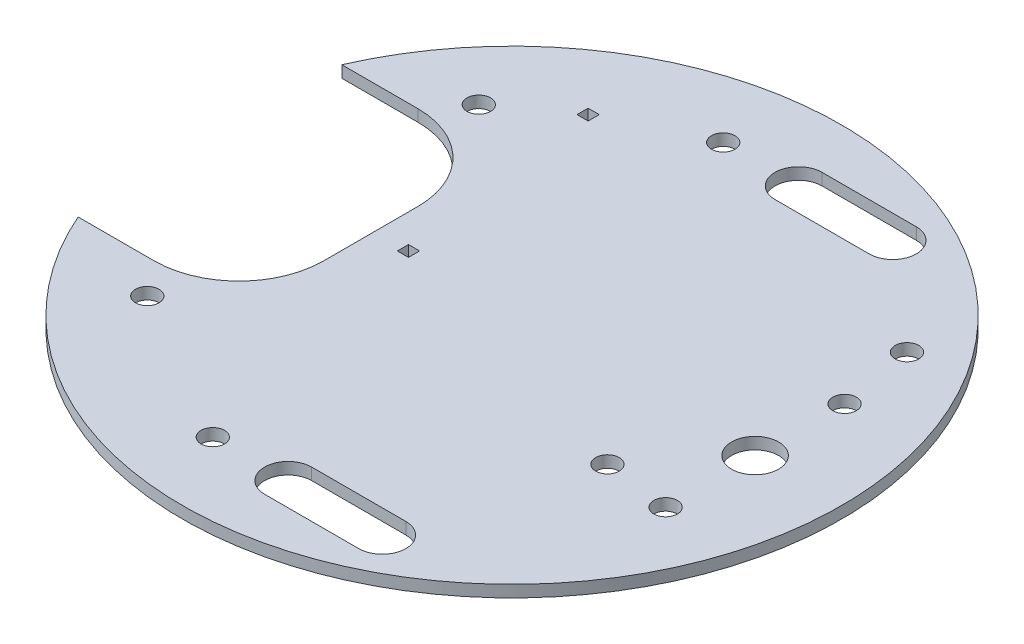
SolidWorks part; units mm, degrees
ref_plane "Front Plane" through (0, 0, 0) normal (0, 0, 1) x (1, 0, 0)
ref_plane "Top Plane" through (0, 0, 0) normal (0, 1, 0) x (1, 0, 0)
ref_plane "Right Plane" through (0, 0, 0) normal (1, 0, 0) x (0, 0, -1)
sketch "Sketch1" plane through (0, 0, 0) normal (0, 1, 0) x (1, 0, 0)
  line L0 (0, 0) -> (109.2336, 0) construction
  line L1 (0, 0) -> (-110.6657, 0) construction
  line L2 (27.076, -24.13) -> (65.5497, -24.13)
  line L3 (27.076, -24.13) -> (27.076, 24.13)
  line L4 (27.076, 24.13) -> (65.5497, 24.13)
  line L5 (65.5497, -24.13) -> (65.5497, 24.13)
  line L6 (27.076, -24.13) -> (65.5497, 24.13) construction
  line L7 (27.076, 24.13) -> (65.5497, -24.13) construction
  line L9 (-88.9, 35.56) -> (-38.1, 35.56)
  line L10 (-88.9, 35.56) -> (-88.9, -35.56)
  line L11 (-88.9, -35.56) -> (-38.1, -35.56)
  line L12 (-38.1, 35.56) -> (-38.1, -35.56)
  line L13 (-88.9, 35.56) -> (-38.1, -35.56) construction
  line L14 (-88.9, -35.56) -> (-38.1, 35.56) construction
  circle A0 centre (0, 0) radius 88.9
  circle A1 centre (0, 0) radius 69.85
  circle A2 centre (65.5497, 24.13) radius 3.175
  circle A3 centre (65.5497, -24.13) radius 3.175
  circle A4 centre (-53.6721, -44.7027) radius 3.175
  circle A5 centre (-11.8777, -68.8327) radius 3.175
  circle A6 centre (-11.8777, 68.8327) radius 3.175
  circle A7 centre (-53.6721, 44.7027) radius 3.175
  point P4 (46.3129, 0)
  point P12 (-63.5, 0)
  point P23 (0, 0)
  dimension "D1" = 177.8
  dimension "D2" = 139.7
  dimension "D4" = 3
  dimension "D3" = 48.26
  dimension "D5" = 71.12
  dimension "D6" = 50.8
  dimension "D7" = 63.5
sketch "Sketch2" plane through (0, 0, 0) normal (0, 1, 0) x (1, 0, 0)
  circle A0 centre (0, 0) radius 88.9
extrude "Boss-Extrude1" add sketch "Sketch2" along normal blind 3.175
sketch "Sketch3" plane through (0, 3.175, 0) normal (0, 1, 0) x (1, 0, 0)
  line L4 (27.076, -24.13) -> (65.5497, -24.13)
  line L5 (65.5497, -24.13) -> (65.5497, 24.13)
  line L6 (65.5497, 24.13) -> (27.076, 24.13)
  line L7 (27.076, 24.13) -> (27.076, -24.13)
  line L8 (27.076, -24.13) -> (65.5497, -24.13)
  line L9 (65.5497, -24.13) -> (65.5497, 24.13)
  line L10 (65.5497, 24.13) -> (27.076, 24.13)
  line L11 (27.076, 24.13) -> (27.076, -24.13)
  line L12 (-38.1, 35.56) -> (-88.9, 35.56)
  line L13 (-38.1, -35.56) -> (-38.1, 35.56)
  line L14 (-88.9, -35.56) -> (-38.1, -35.56)
  line L15 (-88.9, 35.56) -> (-88.9, -35.56)
  line L16 (-38.1, 35.56) -> (-88.9, 35.56)
  line L17 (-38.1, -35.56) -> (-38.1, 35.56)
  line L18 (-88.9, -35.56) -> (-38.1, -35.56)
  line L19 (-88.9, 35.56) -> (-88.9, -35.56)
  circle A1 centre (65.5497, -24.13) radius 3.175
  circle A2 centre (65.5497, -24.13) radius 3.175
  circle A3 centre (65.5497, 24.13) radius 3.175
  circle A4 centre (65.5497, 24.13) radius 3.175
  circle A5 centre (0, 0) radius 69.85
  circle A6 centre (0, 0) radius 69.85
  circle A7 centre (0, 0) radius 88.9
  circle A8 centre (0, 0) radius 88.9
  circle A9 centre (-53.6721, 44.7027) radius 3.175
  circle A10 centre (-53.6721, 44.7027) radius 3.175
  circle A11 centre (-11.8777, 68.8327) radius 3.175
  circle A12 centre (-11.8777, 68.8327) radius 3.175
  circle A13 centre (-11.8777, -68.8327) radius 3.175
  circle A14 centre (-11.8777, -68.8327) radius 3.175
  circle A15 centre (-53.6721, -44.7027) radius 3.175
  circle A16 centre (-53.6721, -44.7027) radius 3.175
  dimension "D1" = 0
  dimension "D2" = 0
  dimension "D3" = 0
  dimension "D4" = 0
  dimension "D5" = 0
  dimension "D6" = 0
  dimension "D7" = 0
  dimension "D8" = 0
  dimension "D9" = 0
  dimension "D10" = 0
extrude "Cut-Extrude1" cut sketch "Sketch3" against normal blind 3.175 contours A10 | A12 | A4 | A2 | A14 | A16 | L16 L19 L18 L17
sketch "Sketch4" plane through (0, 3.175, 0) normal (0, 1, 0) x (1, 0, 0)
  line L0 (0, 88.9) -> (0, -88.9) construction
  line L1 (88.9, 0) -> (-87.6104, 0) construction
  line L2 (52.695, -25.135) -> (52.695, -18.785)
  line L3 (-30.48, 2.54) -> (47.52, 2.54)
  line L4 (-30.48, 2.54) -> (-30.48, -57.46)
  line L5 (-30.48, -57.46) -> (47.52, -57.46)
  line L6 (47.52, 2.54) -> (47.52, -57.46)
  line L7 (-38.1, 58.62) -> (56.9, 58.62)
  line L8 (-38.1, 58.62) -> (-38.1, 7.62)
  line L9 (-38.1, 7.62) -> (56.9, 7.62)
  line L10 (56.9, 58.62) -> (56.9, 7.62)
  line L11 (56.9, 58.62) -> (53.9, 58.62)
  line L12 (56.9, 58.62) -> (56.9, 7.62)
  line L13 (56.9, 7.62) -> (53.9, 7.62)
  line L14 (53.9, 58.62) -> (53.9, 7.62)
  line L15 (56.9, 58.62) -> (61.9, 58.62)
  line L16 (56.9, 58.62) -> (56.9, 44.62)
  line L17 (56.9, 44.62) -> (61.9, 44.62)
  line L18 (61.9, 58.62) -> (61.9, 44.62)
  line L19 (47.52, 2.54) -> (44.52, 2.54)
  line L20 (47.52, 2.54) -> (47.52, -57.46)
  line L21 (47.52, -57.46) -> (44.52, -57.46)
  line L22 (44.52, 2.54) -> (44.52, -57.46)
  line L23 (47.52, 2.54) -> (47.695, 2.54)
  line L24 (47.52, 2.54) -> (47.52, -21.96)
  line L25 (47.52, -21.96) -> (47.695, -21.96)
  line L26 (47.695, 2.54) -> (47.695, -21.96)
  line L27 (52.695, -25.135) -> (42.695, -25.135)
  line L28 (52.695, -18.785) -> (42.695, -18.785)
  line L29 (42.695, -25.135) -> (42.695, -18.785)
  line L30 (52.695, -25.135) -> (42.695, -18.785) construction
  line L31 (52.695, -18.785) -> (42.695, -25.135) construction
  line L32 (69.9, 41.445) -> (69.9, 47.795)
  line L33 (69.9, 41.445) -> (53.9, 41.445)
  line L34 (69.9, 47.795) -> (53.9, 47.795)
  line L35 (53.9, 41.445) -> (53.9, 47.795)
  line L36 (69.9, 41.445) -> (53.9, 47.795) construction
  line L37 (69.9, 47.795) -> (53.9, 41.445) construction
  line L39 (-38.1, 58.62) -> (-35.1, 58.62)
  line L40 (-38.1, 58.62) -> (-38.1, 55.62)
  line L41 (-38.1, 55.62) -> (-35.1, 55.62)
  line L42 (-35.1, 58.62) -> (-35.1, 55.62)
  line L43 (-30.48, 2.54) -> (-27.48, 2.54)
  line L44 (-30.48, 2.54) -> (-30.48, -0.46)
  line L45 (-30.48, -0.46) -> (-27.48, -0.46)
  line L46 (-27.48, 2.54) -> (-27.48, -0.46)
  arc A0 (-81.4782, -35.56) -> (-81.4782, 35.56) centre (0, 0) ccw construction
  circle A1 centre (-53.6721, -44.7027) radius 7.9375
  circle A2 centre (-11.8777, -68.8327) radius 7.9375
  circle A11 centre (47.695, -21.96) radius 3.175
  circle A12 centre (61.9, 44.62) radius 3.175
  circle A13 centre (-11.8777, 68.8327) radius 7.9375
  circle A14 centre (-53.6721, 44.7027) radius 7.9375
  circle A15 centre (65.5497, -24.13) radius 7.9375
  circle A16 centre (65.5497, 24.13) radius 7.9375
  point P33 (0.7332, 3.6329)
  point P34 (0, -3.9109)
  point P61 (0, 0)
  dimension "D1" = 15.875
  dimension "D2" = 15.875
  dimension "D14" = 6.35
  dimension "D18" = 6.35
  dimension "D4" = 78
  dimension "D5" = 60
  dimension "D6" = 2.54
  dimension "D7" = 30.48
  dimension "D8" = 95
  dimension "D9" = 51
  dimension "D10" = 38.1
  dimension "D11" = 7.62
  dimension "D12" = 14
  dimension "D13" = 3
  dimension "D15" = 6.35
  dimension "D16" = 16
  dimension "D17" = 6.35
  dimension "D19" = 10
  dimension "D20" = 24.5
  dimension "D21" = 0.175
  dimension "D22" = 3
  dimension "D23" = 0
  dimension "D24" = 3
  dimension "D25" = 3
  dimension "D26" = 3
  dimension "D27" = 3
  dimension "D3" = 3
sketch "Sketch5" plane through (0, 3.175, 0) normal (0, 1, 0) x (1, 0, 0)
  line L0 (-38.1, 58.62) -> (-38.1, 7.62) construction
  line L1 (-38.1, 7.62) -> (56.9, 7.62) construction
  line L2 (56.9, 58.62) -> (56.9, 7.62) construction
  line L3 (56.9, 58.62) -> (56.9, 7.62) construction
  line L4 (56.9, 58.62) -> (53.9, 58.62) construction
  line L5 (53.9, 58.62) -> (53.9, 7.62) construction
  line L6 (56.9, 7.62) -> (53.9, 7.62) construction
  line L7 (-38.1, 58.62) -> (56.9, 58.62) construction
  line L8 (-30.48, 2.54) -> (-30.48, -57.46) construction
  line L9 (-30.48, -57.46) -> (47.52, -57.46) construction
  line L10 (47.52, 2.54) -> (47.52, -57.46) construction
  line L11 (47.52, 2.54) -> (47.52, -57.46) construction
  line L12 (47.52, 2.54) -> (44.52, 2.54) construction
  line L13 (44.52, 2.54) -> (44.52, -57.46) construction
  line L14 (47.52, -57.46) -> (44.52, -57.46) construction
  line L15 (-30.48, 2.54) -> (47.52, 2.54) construction
  line L16 (-38.1, 58.62) -> (-35.1, 58.62) construction
  line L17 (-35.1, 58.62) -> (-35.1, 55.62) construction
  line L18 (-38.1, 55.62) -> (-35.1, 55.62) construction
  line L19 (-38.1, 58.62) -> (-38.1, 55.62) construction
  line L20 (47.52, 2.54) -> (47.695, 2.54) construction
  line L21 (47.695, 2.54) -> (47.695, -21.96) construction
  line L22 (47.52, -21.96) -> (47.695, -21.96) construction
  line L23 (47.52, 2.54) -> (47.52, -21.96) construction
  line L24 (-30.48, 2.54) -> (-27.48, 2.54) construction
  line L25 (-27.48, 2.54) -> (-27.48, -0.46) construction
  line L26 (-30.48, -0.46) -> (-27.48, -0.46) construction
  line L27 (-30.48, 2.54) -> (-30.48, -0.46) construction
  line L28 (56.9, 58.62) -> (61.9, 58.62) construction
  line L29 (61.9, 58.62) -> (61.9, 44.62) construction
  line L30 (56.9, 44.62) -> (61.9, 44.62) construction
  line L31 (56.9, 58.62) -> (56.9, 44.62) construction
  line L32 (69.9, 41.445) -> (69.9, 47.795) construction
  line L33 (69.9, 47.795) -> (53.9, 47.795) construction
  line L34 (53.9, 41.445) -> (53.9, 47.795) construction
  line L35 (69.9, 41.445) -> (53.9, 41.445) construction
  line L36 (52.695, -25.135) -> (52.695, -18.785) construction
  line L37 (52.695, -18.785) -> (42.695, -18.785) construction
  line L38 (42.695, -25.135) -> (42.695, -18.785) construction
  line L39 (52.695, -25.135) -> (42.695, -25.135) construction
  line L40 (-38.1, 58.62) -> (-38.1, 7.62)
  line L41 (-38.1, 7.62) -> (56.9, 7.62)
  line L42 (56.9, 58.62) -> (56.9, 7.62)
  line L43 (56.9, 58.62) -> (56.9, 7.62)
  line L44 (56.9, 58.62) -> (53.9, 58.62)
  line L45 (53.9, 58.62) -> (53.9, 7.62)
  line L46 (56.9, 7.62) -> (53.9, 7.62)
  line L47 (-38.1, 58.62) -> (56.9, 58.62)
  line L48 (-30.48, 2.54) -> (-30.48, -57.46)
  line L49 (-30.48, -57.46) -> (47.52, -57.46)
  line L50 (47.52, 2.54) -> (47.52, -57.46)
  line L51 (47.52, 2.54) -> (47.52, -57.46)
  line L52 (47.52, 2.54) -> (44.52, 2.54)
  line L53 (44.52, 2.54) -> (44.52, -57.46)
  line L54 (47.52, -57.46) -> (44.52, -57.46)
  line L55 (-30.48, 2.54) -> (47.52, 2.54)
  line L56 (-38.1, 58.62) -> (-35.1, 58.62)
  line L57 (-35.1, 58.62) -> (-35.1, 55.62)
  line L58 (-38.1, 55.62) -> (-35.1, 55.62)
  line L59 (-38.1, 58.62) -> (-38.1, 55.62)
  line L60 (47.52, 2.54) -> (47.695, 2.54)
  line L61 (47.695, 2.54) -> (47.695, -21.96)
  line L62 (47.52, -21.96) -> (47.695, -21.96)
  line L63 (47.52, 2.54) -> (47.52, -21.96)
  line L64 (-30.48, 2.54) -> (-27.48, 2.54)
  line L65 (-27.48, 2.54) -> (-27.48, -0.46)
  line L66 (-30.48, -0.46) -> (-27.48, -0.46)
  line L67 (-30.48, 2.54) -> (-30.48, -0.46)
  line L68 (56.9, 58.62) -> (61.9, 58.62)
  line L69 (61.9, 58.62) -> (61.9, 44.62)
  line L70 (56.9, 44.62) -> (61.9, 44.62)
  line L71 (56.9, 58.62) -> (56.9, 44.62)
  line L72 (69.9, 41.445) -> (69.9, 47.795)
  line L73 (69.9, 47.795) -> (53.9, 47.795)
  line L74 (53.9, 41.445) -> (53.9, 47.795)
  line L75 (69.9, 41.445) -> (53.9, 41.445)
  line L76 (52.695, -25.135) -> (52.695, -18.785)
  line L77 (52.695, -18.785) -> (42.695, -18.785)
  line L78 (42.695, -25.135) -> (42.695, -18.785)
  line L79 (52.695, -25.135) -> (42.695, -25.135)
  circle A0 centre (-11.8777, 68.8327) radius 7.9375
  circle A1 centre (-53.6721, 44.7027) radius 7.9375
  circle A2 centre (65.5497, -24.13) radius 7.9375
  circle A3 centre (-11.8777, -68.8327) radius 7.9375 construction
  circle A4 centre (-53.6721, -44.7027) radius 7.9375 construction
  circle A5 centre (61.9, 44.62) radius 3.175 construction
  circle A6 centre (47.695, -21.96) radius 3.175 construction
  circle A7 centre (65.5497, 24.13) radius 7.9375
  circle A11 centre (-11.8777, -68.8327) radius 7.9375
  circle A12 centre (-53.6721, -44.7027) radius 7.9375
  circle A13 centre (61.9, 44.62) radius 3.175
  circle A14 centre (47.695, -21.96) radius 3.175
  point P30 (0, 0)
  dimension "D1" = 3
extrude "Cut-Extrude2" cut sketch "Sketch5" against normal through all contours L40 L58 L57 L47 | L48 L66 L65 L55 | A13 | A14
fillet "Fillet1" radius 22.86 2 edges at (-38.1, 1.5875, 35.56) (-38.1, 1.5875, -35.56)
sketch "Sketch6" plane through (0, 3.175, 0) normal (0, 1, 0) x (1, 0, 0)
  line L0 (-38.1, 58.62) -> (-38.1, 7.62) construction
  line L1 (-38.1, 7.62) -> (56.9, 7.62) construction
  line L2 (56.9, 58.62) -> (56.9, 7.62) construction
  line L3 (56.9, 58.62) -> (56.9, 7.62) construction
  line L4 (56.9, 58.62) -> (53.9, 58.62) construction
  line L5 (53.9, 58.62) -> (53.9, 7.62) construction
  line L6 (56.9, 7.62) -> (53.9, 7.62) construction
  line L7 (-38.1, 58.62) -> (56.9, 58.62) construction
  line L8 (-30.48, 2.54) -> (-30.48, -57.46) construction
  line L9 (-30.48, -57.46) -> (47.52, -57.46) construction
  line L10 (47.52, 2.54) -> (47.52, -57.46) construction
  line L11 (47.52, 2.54) -> (47.52, -57.46) construction
  line L12 (47.52, 2.54) -> (44.52, 2.54) construction
  line L13 (44.52, 2.54) -> (44.52, -57.46) construction
  line L14 (47.52, -57.46) -> (44.52, -57.46) construction
  line L15 (-30.48, 2.54) -> (47.52, 2.54) construction
  line L16 (-38.1, 58.62) -> (-35.1, 58.62) construction
  line L17 (-35.1, 58.62) -> (-35.1, 55.62) construction
  line L18 (-38.1, 55.62) -> (-35.1, 55.62) construction
  line L19 (-38.1, 58.62) -> (-38.1, 55.62) construction
  line L20 (47.52, 2.54) -> (47.695, 2.54) construction
  line L21 (47.695, 2.54) -> (47.695, -21.96) construction
  line L22 (47.52, -21.96) -> (47.695, -21.96) construction
  line L23 (47.52, 2.54) -> (47.52, -21.96) construction
  line L24 (-30.48, 2.54) -> (-27.48, 2.54) construction
  line L25 (-27.48, 2.54) -> (-27.48, -0.46) construction
  line L26 (-30.48, -0.46) -> (-27.48, -0.46) construction
  line L27 (-30.48, 2.54) -> (-30.48, -0.46) construction
  line L28 (56.9, 58.62) -> (61.9, 58.62) construction
  line L29 (61.9, 58.62) -> (61.9, 44.62) construction
  line L30 (56.9, 44.62) -> (61.9, 44.62) construction
  line L31 (56.9, 58.62) -> (56.9, 44.62) construction
  line L32 (69.9, 41.445) -> (69.9, 47.795) construction
  line L33 (69.9, 47.795) -> (53.9, 47.795) construction
  line L34 (53.9, 41.445) -> (53.9, 47.795) construction
  line L35 (69.9, 41.445) -> (53.9, 41.445) construction
  line L36 (52.695, -25.135) -> (52.695, -18.785) construction
  line L37 (52.695, -18.785) -> (42.695, -18.785) construction
  line L38 (42.695, -25.135) -> (42.695, -18.785) construction
  line L39 (52.695, -25.135) -> (42.695, -25.135) construction
  line L40 (-38.1, 58.62) -> (-38.1, 7.62)
  line L41 (-38.1, 7.62) -> (56.9, 7.62)
  line L42 (56.9, 58.62) -> (56.9, 7.62)
  line L43 (56.9, 58.62) -> (56.9, 7.62)
  line L44 (56.9, 58.62) -> (53.9, 58.62)
  line L45 (53.9, 58.62) -> (53.9, 7.62)
  line L46 (56.9, 7.62) -> (53.9, 7.62)
  line L47 (-38.1, 58.62) -> (56.9, 58.62)
  line L48 (-30.48, 2.54) -> (-30.48, -57.46)
  line L49 (-30.48, -57.46) -> (47.52, -57.46)
  line L50 (47.52, 2.54) -> (47.52, -57.46)
  line L51 (47.52, 2.54) -> (47.52, -57.46)
  line L52 (47.52, 2.54) -> (44.52, 2.54)
  line L53 (44.52, 2.54) -> (44.52, -57.46)
  line L54 (47.52, -57.46) -> (44.52, -57.46)
  line L55 (-30.48, 2.54) -> (47.52, 2.54)
  line L56 (-38.1, 58.62) -> (-35.1, 58.62)
  line L57 (-35.1, 58.62) -> (-35.1, 55.62)
  line L58 (-38.1, 55.62) -> (-35.1, 55.62)
  line L59 (-38.1, 58.62) -> (-38.1, 55.62)
  line L60 (47.52, 2.54) -> (47.695, 2.54)
  line L61 (47.695, 2.54) -> (47.695, -21.96)
  line L62 (47.52, -21.96) -> (47.695, -21.96)
  line L63 (47.52, 2.54) -> (47.52, -21.96)
  line L64 (-30.48, 2.54) -> (-27.48, 2.54)
  line L65 (-27.48, 2.54) -> (-27.48, -0.46)
  line L66 (-30.48, -0.46) -> (-27.48, -0.46)
  line L67 (-30.48, 2.54) -> (-30.48, -0.46)
  line L68 (56.9, 58.62) -> (61.9, 58.62)
  line L69 (61.9, 58.62) -> (61.9, 44.62)
  line L70 (56.9, 44.62) -> (61.9, 44.62)
  line L71 (56.9, 58.62) -> (56.9, 44.62)
  line L72 (69.9, 41.445) -> (69.9, 47.795)
  line L73 (69.9, 47.795) -> (53.9, 47.795)
  line L74 (53.9, 41.445) -> (53.9, 47.795)
  line L75 (69.9, 41.445) -> (53.9, 41.445)
  line L76 (52.695, -25.135) -> (52.695, -18.785)
  line L77 (52.695, -18.785) -> (42.695, -18.785)
  line L78 (42.695, -25.135) -> (42.695, -18.785)
  line L79 (52.695, -25.135) -> (42.695, -25.135)
  line L80 (8.4423, 68.8327) -> (33.8423, 68.8327) construction
  line L81 (8.4423, 75.1827) -> (33.8423, 75.1827)
  line L82 (8.4423, 62.4827) -> (33.8423, 62.4827)
  line L83 (8.4423, -68.8327) -> (33.8423, -68.8327) construction
  line L84 (8.4423, -62.4827) -> (33.8423, -62.4827)
  line L85 (8.4423, -75.1827) -> (33.8423, -75.1827)
  line L86 (0, 0) -> (103.5857, 0) construction
  line L87 (21.1423, 91.3998) -> (21.1423, -92.9891) construction
  line L88 (65.5497, 24.13) -> (65.5497, -24.13) construction
  line L89 (-11.8777, 68.8327) -> (21.1423, 68.8327)
  line L90 (-11.8777, -68.8327) -> (21.1423, -68.8327)
  circle A0 centre (-53.6721, 44.7027) radius 7.9375 construction
  circle A1 centre (-11.8777, 68.8327) radius 7.9375 construction
  circle A2 centre (-11.8777, -68.8327) radius 7.9375 construction
  circle A3 centre (-53.6721, -44.7027) radius 7.9375 construction
  circle A4 centre (65.5497, -24.13) radius 7.9375 construction
  circle A5 centre (61.9, 44.62) radius 3.175 construction
  circle A6 centre (47.695, -21.96) radius 3.175 construction
  circle A7 centre (65.5497, 24.13) radius 7.9375 construction
  circle A8 centre (-53.6721, 44.7027) radius 7.9375
  circle A9 centre (-11.8777, 68.8327) radius 7.9375
  circle A10 centre (-11.8777, -68.8327) radius 7.9375
  circle A11 centre (-53.6721, -44.7027) radius 7.9375
  circle A12 centre (65.5497, -24.13) radius 7.9375
  circle A13 centre (61.9, 44.62) radius 3.175
  circle A14 centre (47.695, -21.96) radius 3.175
  circle A15 centre (65.5497, 24.13) radius 7.9375
  arc A16 (8.4423, 75.1827) -> (8.4423, 62.4827) centre (8.4423, 68.8327) ccw
  arc A17 (33.8423, 62.4827) -> (33.8423, 75.1827) centre (33.8423, 68.8327) ccw
  arc A18 (8.4423, -62.4827) -> (8.4423, -75.1827) centre (8.4423, -68.8327) ccw
  arc A19 (33.8423, -75.1827) -> (33.8423, -62.4827) centre (33.8423, -68.8327) ccw
  circle A20 centre (65.5497, 0) radius 6.35
  point P22 (21.1423, 68.8327)
  point P31 (21.1423, -68.8327)
  dimension "D3" = 6.35
  dimension "D5" = 6.35
  dimension "D6" = 12.7
  dimension "D1" = 33.02
  dimension "D2" = 25.4
  dimension "D4" = 25.4
extrude "Cut-Extrude3" cut sketch "Sketch6" against normal through all
